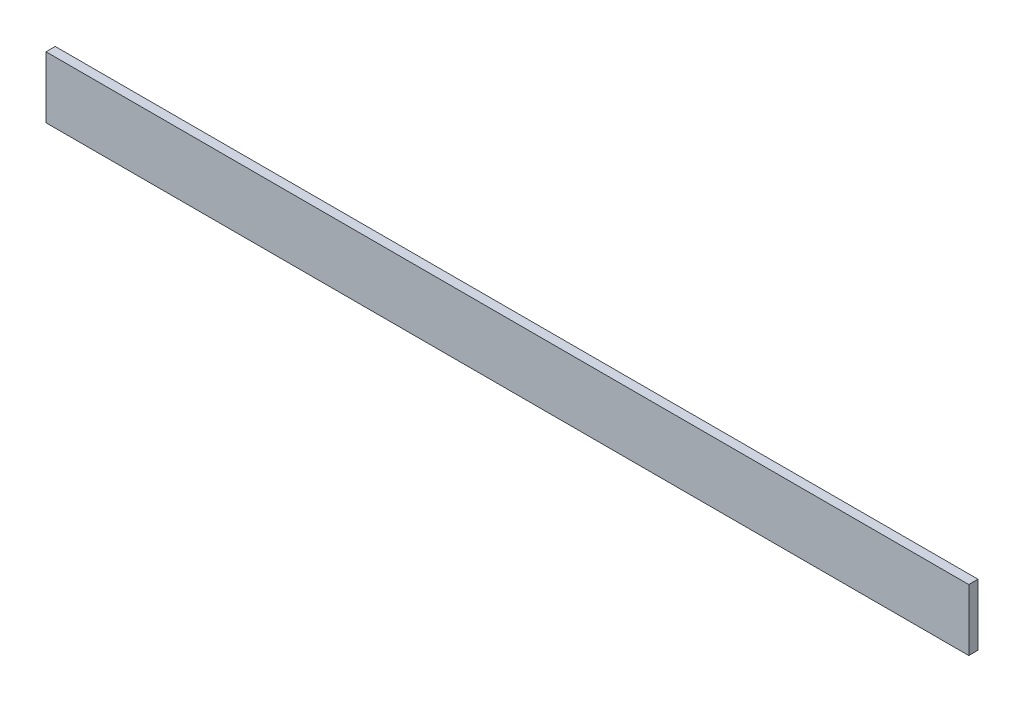
SolidWorks part; units mm, degrees
ref_plane "Alzado" through (0, 0, 0) normal (0, 0, 1) x (1, 0, 0)
ref_plane "Planta" through (0, 0, 0) normal (0, 1, 0) x (1, 0, 0)
ref_plane "Vista lateral" through (0, 0, 0) normal (1, 0, 0) x (0, 0, -1)
sketch "Sketch1" plane through (0, 0, 0) normal (0, 0, 1) x (1, 0, 0)
  line L1 (-150, -10) -> (150, -10)
  line L2 (-150, -10) -> (-150, 10)
  line L3 (-150, 10) -> (150, 10)
  line L4 (150, -10) -> (150, 10)
  line L5 (-150, -10) -> (150, 10) construction
  line L6 (-150, 10) -> (150, -10) construction
  point P0 (0, 0)
  dimension "D1" = 300
  dimension "D2" = 20
extrude "Boss-Extrude1" add sketch "Sketch1" along normal blind 3
